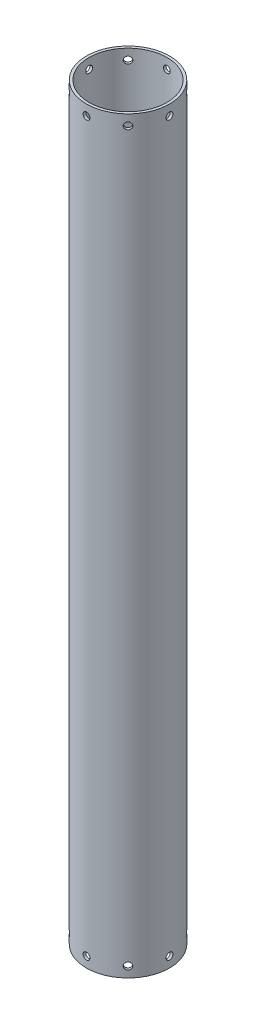
SolidWorks part; units mm, degrees
material "6061-T6 (SS)"
ref_plane "Front Plane" through (0, 0, 0) normal (0, 0, 1) x (1, 0, 0)
ref_plane "Top Plane" through (0, 0, 0) normal (0, 1, 0) x (1, 0, 0)
ref_plane "Right Plane" through (0, 0, 0) normal (1, 0, 0) x (0, 0, -1)
sketch "Sketch1" plane through (0, 0, 0) normal (0, 1, 0) x (1, 0, 0)
  circle A0 centre (0, 0) radius 50.8
  circle A1 centre (0, 0) radius 47.625
  dimension "D1" = 101.6
  dimension "D2" = 95.25
extrude "Boss-Extrude1" add sketch "Sketch1" along normal blind 914.4
ref_plane "Plane1" through (0, 0, 50.8) normal (0, 0, 1) x (1, 0, 0)
hole_wizard "21/64 (0.32813) Diameter Hole1" positions "Sketch2" profile "Sketch3" hole size "21/64" standard "ANSI Inch"
sketch "Sketch2" plane through (0, 0, 50.8) normal (0, 0, 1) x (1, 0, 0)
  line L0 (47.625, 914.4) -> (-47.625, 914.4) construction
  point P0 (0, 12.7)
  point P2 (0, 901.7)
  dimension "D1" = 12.7
  dimension "D2" = 12.7
sketch "Sketch3" plane through (0, 12.7, 50.8) normal (1, 0, 0) x (0, -1, 0)
  line L0 (0, 0) -> (0, 7.62)
  line L1 (0, 7.62) -> (4.1673, 5.1161)
  line L2 (4.1673, 5.1161) -> (4.1673, 0)
  line L5 (4.1673, 0) -> (0, 0)
  line L10 (0, 7.62) -> (-4.1673, 5.1161) construction
  line L11 (0, -6.35) -> (0, 107.95) construction
  dimension "Hole Dia." = 8.3345
  dimension "Hole Depth" = 7.62
  dimension "Drill Angle" = 118
pattern_circular "CirPattern1" count 8 over 360 about axis through (0, 914.4, 0) along (0, -1, 0) of "21/64 (0.32813) Diameter Hole1"
ref_plane "Plane2" through (0, 0, -50.8) normal (0, 0, -1) x (-1, 0, 0)
hole_wizard "Ø1.2 (1.2) Diameter Hole1" positions "Sketch7" profile "Sketch8" hole size "Ø1.2" standard "ANSI Metric"
sketch "Sketch7" plane through (0, 0, -50.8) normal (0, 0, -1) x (-1, 0, 0)
  line L0 (0, 914.4) -> (0, 552.45)
  line L1 (47.625, 914.4) -> (-47.625, 914.4) construction
  point P0 (0, 552.45)
  dimension "D1" = 361.95
sketch "Sketch8" plane through (0, 552.45, -50.8) normal (1, 0, 0) x (0, 1, 0)
  line L0 (0, 0) -> (0, 3.175)
  line L1 (0, 3.175) -> (0.6, 3.175)
  line L2 (0.6, 3.175) -> (0.6, 0)
  line L5 (0.6, 0) -> (0, 0)
  line L11 (0, -6.35) -> (0, 107.95) construction
  dimension "Thru Hole Dia." = 1.2
  dimension "Thru Hole Depth" = 3.175
